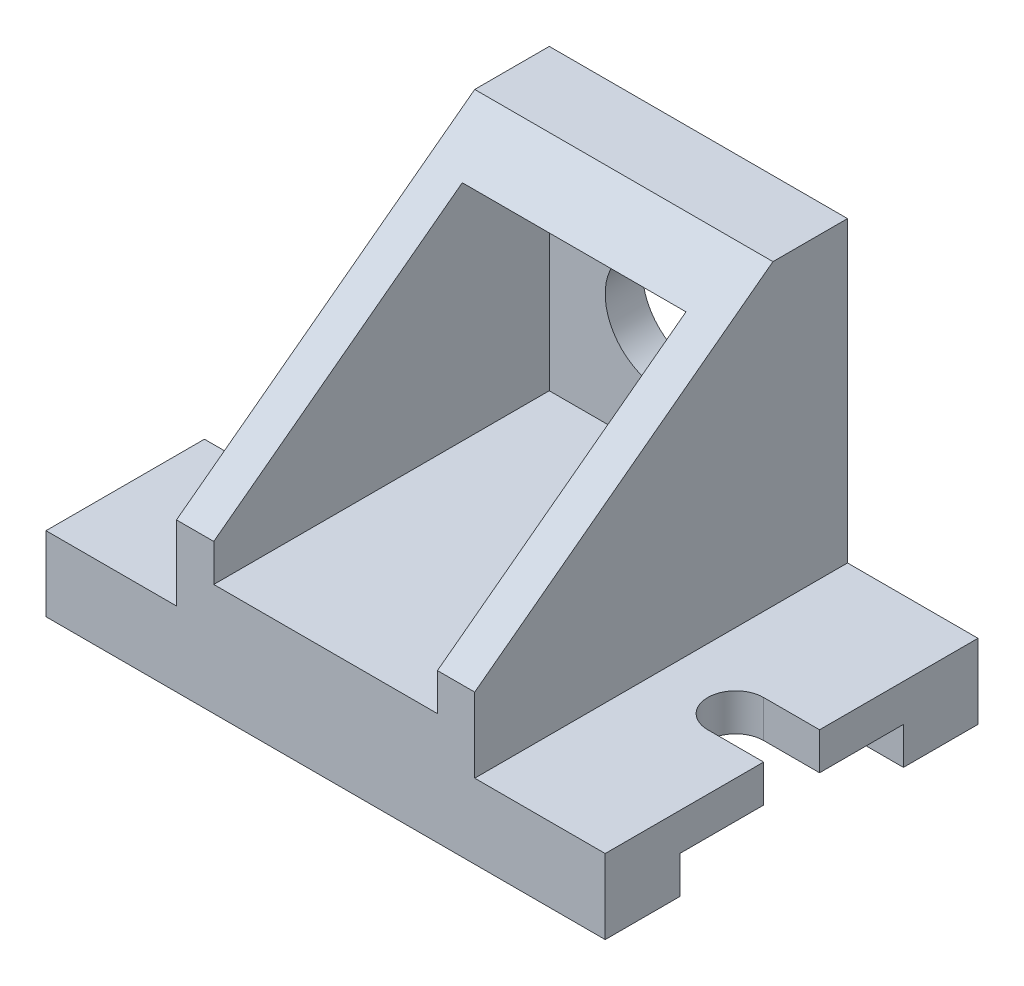
SolidWorks part; units mm, degrees
ref_plane "Front Plane" through (0, 0, 0) normal (0, 0, 1) x (1, 0, 0)
ref_plane "Top Plane" through (0, 0, 0) normal (0, 1, 0) x (1, 0, 0)
ref_plane "Right Plane" through (0, 0, 0) normal (1, 0, 0) x (0, 0, -1)
sketch "Sketch1" plane through (0, 0, 0) normal (1, 0, 0) x (0, 0, -1)
  line L0 (-50, 0) -> (0, 0) construction
  line L1 (50, -10) -> (30, -10)
  line L2 (50, -10) -> (50, 10)
  line L3 (50, 10) -> (-50, 10)
  line L4 (-50, -10) -> (-50, 10)
  line L5 (0, 0) -> (0, -10) construction
  line L6 (-30, -10) -> (-30, 0)
  line L7 (-30, 0) -> (30, 0)
  line L8 (30, -10) -> (30, 0)
  line L9 (-30, -10) -> (-50, -10)
  point P0 (0, 0)
  point P14 (0, 0)
  dimension "D1" = 100
  dimension "D2" = 20
  dimension "D3" = 60
  dimension "D4" = 10
extrude "Boss-Extrude1" add sketch "Sketch1" along normal blind 150
ref_plane "Plane1" through (35, 0, 0) normal (-1, 0, 0) x (0, 0, 1)
sketch "Sketch2" plane through (35, 0, 0) normal (-1, 0, 0) x (0, 0, 1)
  line L0 (50, 10) -> (50, 30)
  line L1 (50, -10) -> (30, -10) construction
  line L2 (50, 30) -> (-30, 90)
  line L3 (-30, 90) -> (-50, 90)
  line L4 (-30, -10) -> (-50, -10) construction
  line L5 (-50, 90) -> (-50, 10)
  line L6 (-50, 10) -> (50, 10)
  dimension "D1" = 40
  dimension "D2" = 20
  dimension "D3" = 100
extrude "Boss-Extrude2" add sketch "Sketch2" against normal blind 80
ref_plane "Plane2" through (0, 0, -40) normal (0, 0, -1) x (-1, 0, 0)
sketch "Sketch3" plane through (0, 0, -40) normal (0, 0, -1) x (-1, 0, 0)
  line L0 (-115, 90) -> (-35, 90) construction
  line L1 (-105, 20) -> (-45, 20)
  line L2 (-105, 20) -> (-105, 80)
  line L3 (-105, 80) -> (-45, 80)
  line L4 (-45, 20) -> (-45, 80)
  line L5 (-105, 20) -> (-45, 80) construction
  line L6 (-105, 80) -> (-45, 20) construction
  line L7 (-150, -10) -> (0, -10) construction
  point P0 (-75, 50)
  point P7 (-75, 90)
  dimension "D1" = 60
  dimension "D2" = 60
  dimension "D3" = 60
extrude "Cut-Extrude1" cut sketch "Sketch3" against normal through all
sketch "Sketch4" plane through (0, 0, -40) normal (0, 0, 1) x (1, 0, 0)
  line L0 (115, 30) -> (115, 90) construction
  line L1 (150, -10) -> (0, -10) construction
  circle A0 centre (75, 50) radius 15
  dimension "D1" = 30
  dimension "D2" = 40
  dimension "D3" = 60
extrude "Cut-Extrude2" cut sketch "Sketch4" against normal blind 80
sketch "Sketch5" plane through (0, 10, 0) normal (0, 1, 0) x (1, 0, 0)
  line L0 (75, -50) -> (75, 50) construction
  line L1 (105, -50) -> (45, -50) construction
  line L2 (115, 50) -> (35, 50) construction
  line L3 (0, 50) -> (0, -50) construction
  line L4 (15, 7.5) -> (0, 7.5)
  line L5 (15, -7.5) -> (0, -7.5)
  line L6 (0, -7.5) -> (0, 7.5)
  line L7 (150, -7.5) -> (150, 7.5)
  line L8 (135, -7.5) -> (150, -7.5)
  line L9 (135, 7.5) -> (150, 7.5)
  arc A0 (15, -7.5) -> (15, 7.5) centre (15, 0) ccw
  arc A1 (135, -7.5) -> (135, 7.5) centre (135, 0) cw
  dimension "D1" = 15
  dimension "D2" = 15
extrude "Cut-Extrude3" cut sketch "Sketch5" against normal through all
